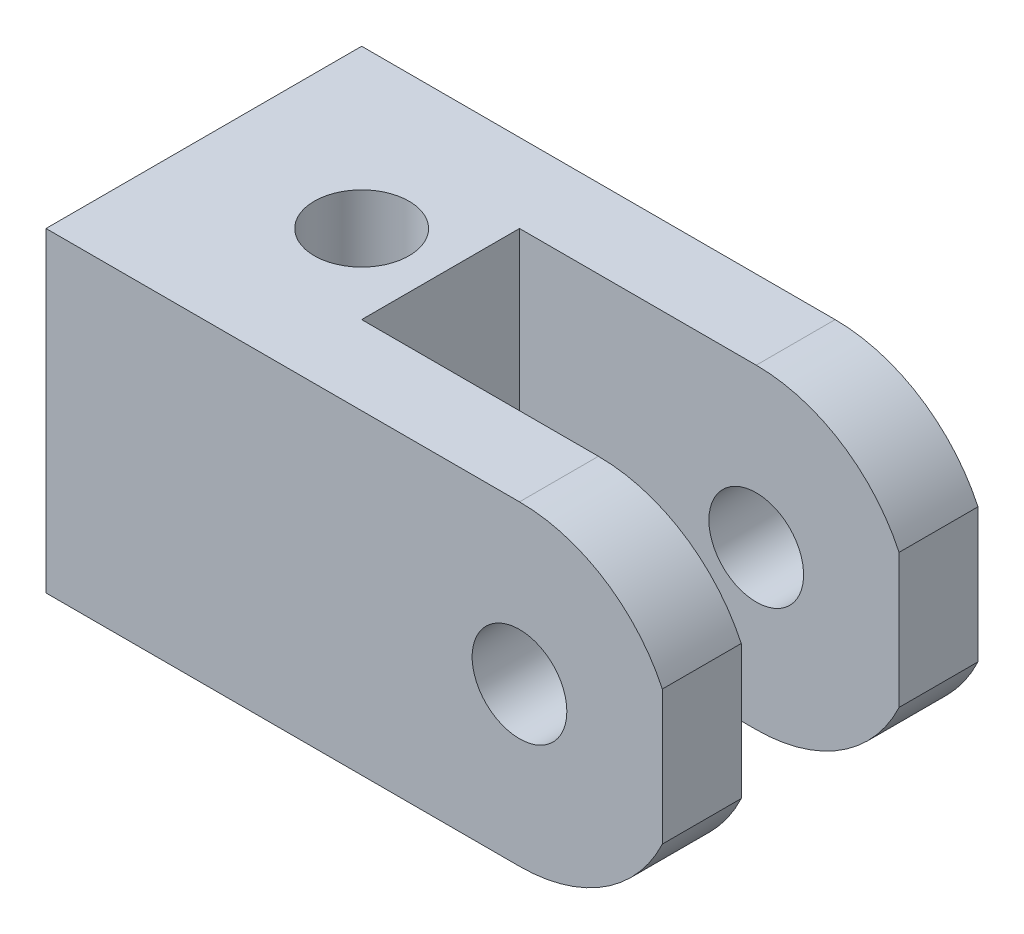
SolidWorks part; units mm, degrees
ref_plane "Alzado" through (0, 0, 0) normal (0, 0, 1) x (1, 0, 0)
ref_plane "Planta" through (0, 0, 0) normal (0, 1, 0) x (1, 0, 0)
ref_plane "Vista lateral" through (0, 0, 0) normal (1, 0, 0) x (0, 0, -1)
sketch "Croquis1" plane through (0, 0, 0) normal (0, 0, 1) x (1, 0, 0)
  line L1 (5, -5) -> (-15, -5)
  line L2 (5, -5) -> (5, 5)
  line L3 (5, 5) -> (-15, 5)
  line L4 (-15, -5) -> (-15, 5)
  circle A0 centre (0, 0) radius 1.5
  dimension "D2" = 3
  dimension "D1" = 20
  dimension "D3" = 10
  dimension "D4" = 5
  dimension "D5" = 5
extrude "Saliente-Extruir1" add sketch "Croquis1" along normal blind 10
sketch "Croquis2" plane through (0, 5, 0) normal (0, 1, 0) x (1, 0, 0)
  line L0 (-15, -10) -> (-15, 0) construction
  line L1 (5, 0) -> (-15, 0) construction
  circle A0 centre (-10, -5) radius 1.5
  dimension "D3" = 3
  dimension "D1" = 5
  dimension "D2" = 5
extrude "Cortar-Extruir1" cut sketch "Croquis2" against normal blind 14
sketch "Croquis3" plane through (5, 0, 0) normal (1, 0, 0) x (0, 0, -1)
  line L0 (-10, -5) -> (0, -5) construction
  line L1 (-7.5, -5) -> (-2.5, -5)
  line L2 (-7.5, -5) -> (-7.5, 5)
  line L3 (-7.5, 5) -> (-2.5, 5)
  line L4 (-2.5, -5) -> (-2.5, 5)
  line L5 (-10, -5) -> (-10, 5) construction
  line L6 (0, -5) -> (0, 5) construction
  dimension "D1" = 2.5
  dimension "D2" = 2.5
  dimension "D3" = 10
extrude "Cortar-Extruir2" cut sketch "Croquis3" against normal blind 12.5
sketch "Sketch1" plane through (0, 0, 10) normal (0, 0, 1) x (1, 0, 0)
  line L0 (0, 5) -> (0, -7.1106) construction
  line L1 (0, 5) -> (5.9929, 5)
  line L2 (5.9929, 5) -> (5.9929, -6.7488)
  line L3 (5.9929, -6.7488) -> (0, -5)
  line L4 (4.5251, 2.1269) -> (4.5251, -2.1269)
  arc A0 (0, -5) -> (4.5251, -2.1269) centre (0, 0) ccw
  arc A1 (4.5251, 2.1269) -> (0, 5) centre (0, 0) ccw
  dimension "D1" = 4.5251
extrude "Cut-Extrude1" cut sketch "Sketch1" against normal blind 10
